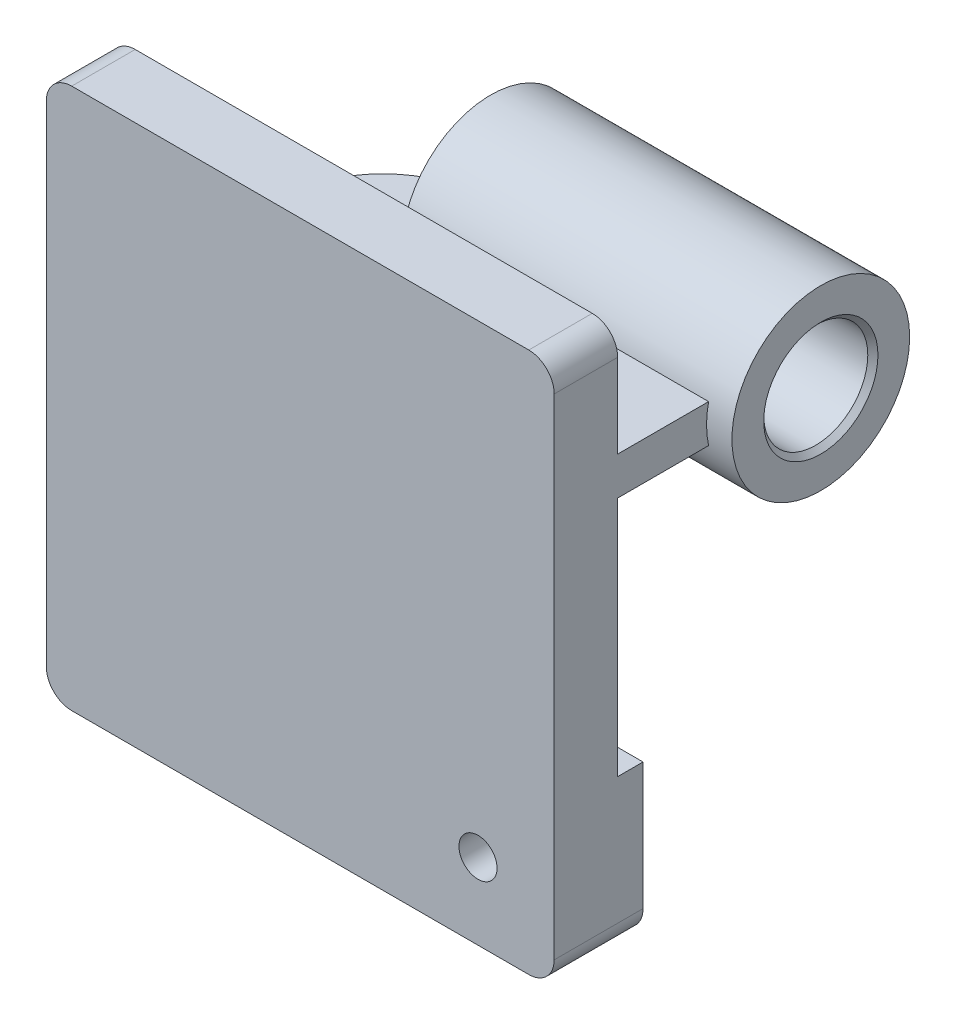
SolidWorks part; units mm, degrees
ref_plane "Front Plane" through (0, 0, 0) normal (0, 0, 1) x (1, 0, 0)
ref_plane "Top Plane" through (0, 0, 0) normal (0, 1, 0) x (1, 0, 0)
ref_plane "Right Plane" through (0, 0, 0) normal (1, 0, 0) x (0, 0, -1)
sketch "Sketch1" plane through (0, 0, 0) normal (0, 0, 1) x (1, 0, 0)
  line L1 (-100, -106.5) -> (100, -106.5)
  line L2 (-100, -106.5) -> (-100, 106.5)
  line L3 (-100, 106.5) -> (100, 106.5)
  line L4 (100, -106.5) -> (100, 106.5)
  line L5 (-100, -106.5) -> (100, 106.5) construction
  line L6 (-100, 106.5) -> (100, -106.5) construction
  point P0 (0, 0)
  dimension "D1" = 200
  dimension "D2" = 213
extrude "Boss-Extrude1" add sketch "Sketch1" along normal blind 25
sketch "Sketch2" plane through (0, 0, 0) normal (0, 0, 1) x (1, 0, 0)
  line L0 (100, -46.5) -> (55, -46.5)
  line L1 (100, -106.5) -> (100, 106.5) construction
  line L2 (40, -61.5) -> (40, -106.5)
  line L3 (-100, -106.5) -> (100, -106.5) construction
  line L4 (40, -106.5) -> (100, -106.5)
  line L5 (100, -106.5) -> (100, -46.5)
  arc A0 (55, -46.5) -> (40, -61.5) centre (55, -61.5) ccw
  point P11 (40, -46.5)
  dimension "D3" = 15
  dimension "D1" = 60
  dimension "D2" = 60
extrude "Boss-Extrude2" add sketch "Sketch2" against normal blind 10
sketch "Sketch3" plane through (0, 0, 0) normal (0, 0, -1) x (-1, 0, 0)
  line L0 (-100, 63.5) -> (-20, 63.5)
  line L1 (-100, -46.5) -> (-100, 106.5) construction
  line L2 (70, -106.5) -> (70, -26.5)
  line L3 (70, -106.5) -> (55, -106.5)
  line L4 (100, -106.5) -> (-40, -106.5) construction
  line L5 (-100, 63.5) -> (-100, 48.5)
  line L7 (-100, 48.5) -> (-35, 48.5)
  line L8 (55, -106.5) -> (55, -41.5)
  arc A0 (70, -26.5) -> (-20, 63.5) centre (70, 63.5) cw
  arc A1 (55, -41.5) -> (-35, 48.5) centre (73.9484, 67.4484) cw
  point P17 (6.3604, -0.1396)
  point P18 (-4.2462, -10.7462)
  dimension "D3" = 90
  dimension "D8" = 15
  dimension "D9" = 65
  dimension "D1" = 80
  dimension "D2" = 80
  dimension "D4" = 170
  dimension "D5" = 170
  dimension "D6" = 15
  dimension "D7" = 15
  dimension "D10" = 65
  dimension "D11" = 65
  dimension "D12" = 21.2132
extrude "Boss-Extrude3" add sketch "Sketch3" along normal blind 70
sketch "Sketch4" plane through (0, 0, 0) normal (0, 0, -1) x (-1, 0, 0)
  line L18 (-42.3237, 39.5) -> (-91, 39.5)
  line L19 (-91, 39.5) -> (-91, -37.5)
  line L20 (-91, -37.5) -> (-55, -37.5)
  line L21 (-31, -61.5) -> (-31, -97.5)
  line L22 (-31, -97.5) -> (46, -97.5)
  line L23 (46, -97.5) -> (46, -48.8237)
  line L24 (-42.3237, 39.5) -> (-91, 39.5)
  line L25 (-91, 39.5) -> (-91, -37.5)
  line L26 (-91, -37.5) -> (-55, -37.5)
  line L27 (-31, -61.5) -> (-31, -97.5)
  line L28 (-31, -97.5) -> (46, -97.5)
  line L29 (46, -97.5) -> (46, -48.8237)
  arc A6 (-42.3237, 39.5) -> (46, -48.8237) centre (73.9484, 67.4484) ccw
  arc A7 (-31, -61.5) -> (-55, -37.5) centre (-55, -61.5) ccw
  arc A8 (-42.3237, 39.5) -> (46, -48.8237) centre (73.9484, 67.4484) ccw
  arc A9 (-31, -61.5) -> (-55, -37.5) centre (-55, -61.5) ccw
  dimension "D1" = 9
extrude "Cut-Extrude1" cut sketch "Sketch4" against normal blind 20
sketch "Sketch5" plane through (100, 0, 0) normal (1, 0, 0) x (0, 0, -1)
  line L0 (70, 63.5) -> (70, 48.5) construction
  circle A0 centre (70, 56) radius 35
  dimension "D1" = 70
extrude "Boss-Extrude5" add sketch "Sketch5" against normal blind 120 and the other way blind 10
sketch "Sketch6" plane through (0, -106.5, 0) normal (0, -1, 0) x (1, 0, 0)
  line L0 (-55, -70) -> (-70, -70) construction
  circle A0 centre (-62.5, -70) radius 41.5
  dimension "D1" = 83
extrude "Boss-Extrude6" add sketch "Sketch6" along normal blind 10 and the other way blind 120
sketch "Sketch7" plane through (0, -116.5, 0) normal (0, -1, 0) x (1, 0, 0)
  circle A0 centre (-62.5, -70) radius 20.5
  dimension "D1" = 41
extrude "Cut-Extrude2" cut sketch "Sketch7" against normal up to next
sketch "Sketch8" plane through (-20, 0, 0) normal (-1, 0, 0) x (0, 0, 1)
  circle A0 centre (-70, 56) radius 20.5
  dimension "D1" = 41
extrude "Cut-Extrude3" cut sketch "Sketch8" against normal up to next
hole_wizard "CBORE for M8 Hex Head Bolt1" positions "3DSketch1" profile "Sketch11" counterbore size "M8" standard "ANSI Metric" end condition through all
sketch3d "3DSketch1"
  line L0 (40, -106.5, -10) -> (100, -106.5, -10) construction
  line L1 (40, -61.5, -10) -> (40, -106.5, -10) construction
  point P0 (70, -76.5, -10)
  point P2 (70, -76.5, -10)
  point P9 (70, -76.5, -10)
  dimension "D1" = 30
  dimension "D2" = 30
sketch "Sketch11" plane through (70, -76.5, -10) normal (1, 0, 0) x (0, 1, 0)
  line L0 (0, 0) -> (0, 35)
  line L1 (0, 35) -> (7.5, 35)
  line L3 (7.5, 35) -> (7.5, 10)
  line L4 (7.5, 10) -> (15, 10)
  line L5 (15, 10) -> (15, 0)
  line L7 (15, 0) -> (0, 0)
  line L11 (0, -6.35) -> (0, 107.95) construction
  dimension "Thru Hole Dia." = 15
  dimension "Thru Hole Depth" = 35
  dimension "C'Bore Dia." = 30
  dimension "C'Bore Depth" = 10
chamfer "Chamfer1" distance 2 angle 45 4 edges at (-62.5, 13.5, -90.5) (-62.5, -116.5, -90.5) (-20, 56, -49.5) (110, 56, -90.5)
fillet "Fillet1" radius 10 10 edges at (91, 39.5, 10) (42.3237, 39.5, 10) (-46, -48.8237, 10) (91, -37.5, 10) (31, -97.5, 10) (-46, -97.5, 10) (100, 106.5, 12.5) (-100, 106.5, 12.5) (-100, -106.5, 12.5) (100, -106.5, 7.5)
